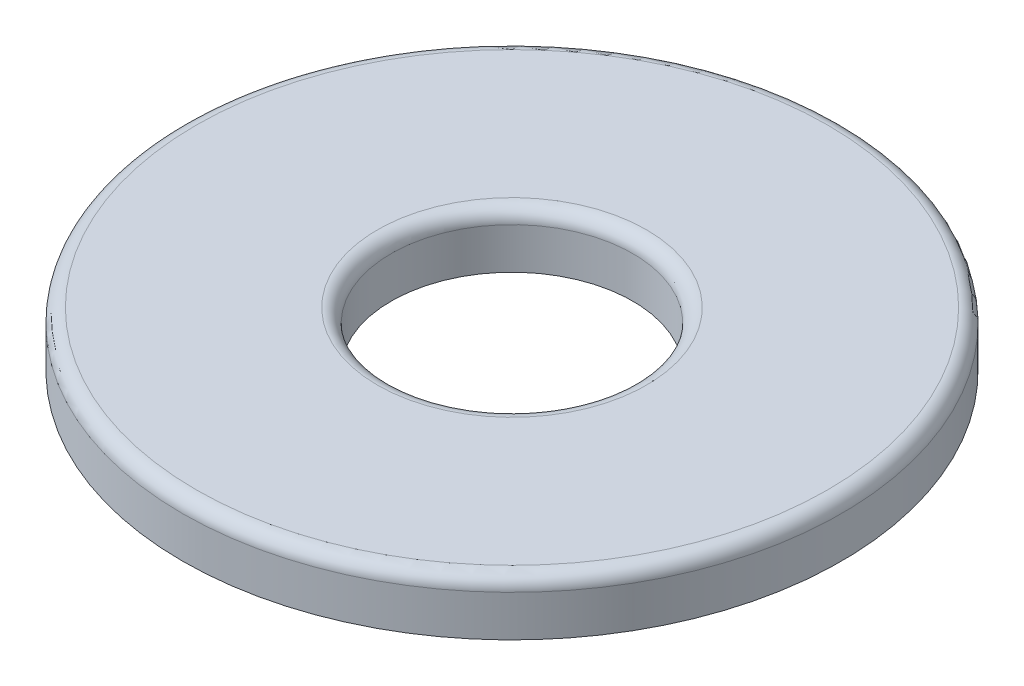
SolidWorks part; units mm, degrees
material "AISI Typ 316L stal nierdzewna"
ref_plane "Płaszczyzna przednia" through (0, 0, 0) normal (0, 0, 1) x (1, 0, 0)
ref_plane "Płaszczyzna górna" through (0, 0, 0) normal (0, 1, 0) x (1, 0, 0)
ref_plane "Płaszczyzna prawa" through (0, 0, 0) normal (1, 0, 0) x (0, 0, -1)
sketch "Szkic1" plane through (0, 0, 0) normal (0, 1, 0) x (1, 0, 0)
  circle A0 centre (0, 0) radius 6
  circle A1 centre (0, 0) radius 2.2
  dimension "D1" = 12
  dimension "D2" = 4.4
extrude "Dodanie-wyciągnięcie1" add sketch "Szkic1" along normal blind 1
fillet "Zaokrąglenie1" radius 0.25 2 edges at (0, 1, 2.2) (0, 1, 6)
